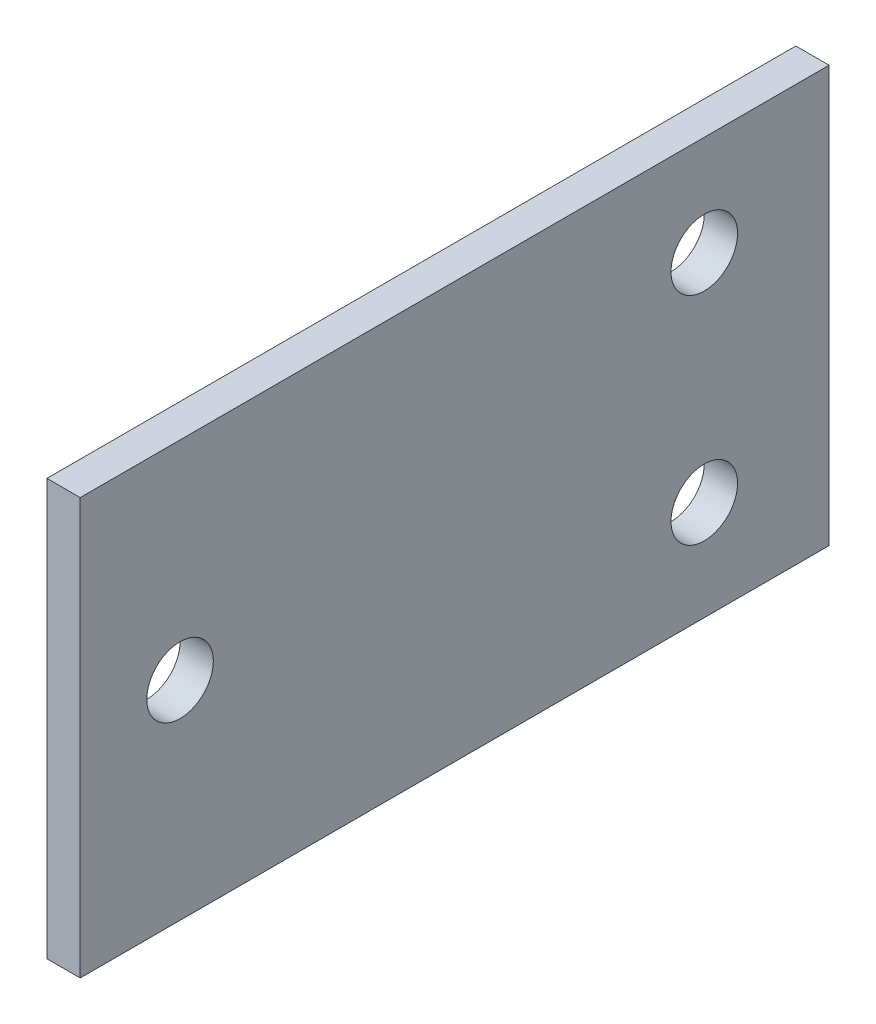
SolidWorks part; units mm, degrees
material "Galvanized Steel"
ref_plane "Front Plane" through (0, 0, 0) normal (0, 0, 1) x (1, 0, 0)
ref_plane "Top Plane" through (0, 0, 0) normal (0, 1, 0) x (1, 0, 0)
ref_plane "Right Plane" through (0, 0, 0) normal (1, 0, 0) x (0, 0, -1)
sketch "Sketch1" plane through (0, 0, 0) normal (0, 1, 0) x (1, 0, 0)
  line L1 (2, -45) -> (-2, -45)
  line L2 (2, -45) -> (2, 45)
  line L3 (2, 45) -> (-2, 45)
  line L4 (-2, -45) -> (-2, 45)
  line L5 (2, -45) -> (-2, 45) construction
  line L6 (2, 45) -> (-2, -45) construction
  point P0 (0, 0)
  dimension "D1" = 4
  dimension "D2" = 90
extrude "Boss-Extrude1" add sketch "Sketch1" along normal blind 50
sketch "Sketch2" plane through (2, 0, 0) normal (1, 0, 0) x (0, 0, -1)
  circle A0 centre (-33, 25) radius 4
  circle A1 centre (30, 38) radius 4
  circle A2 centre (30, 12) radius 4
extrude "Cut-Extrude1" cut sketch "Sketch2" against normal blind 10
